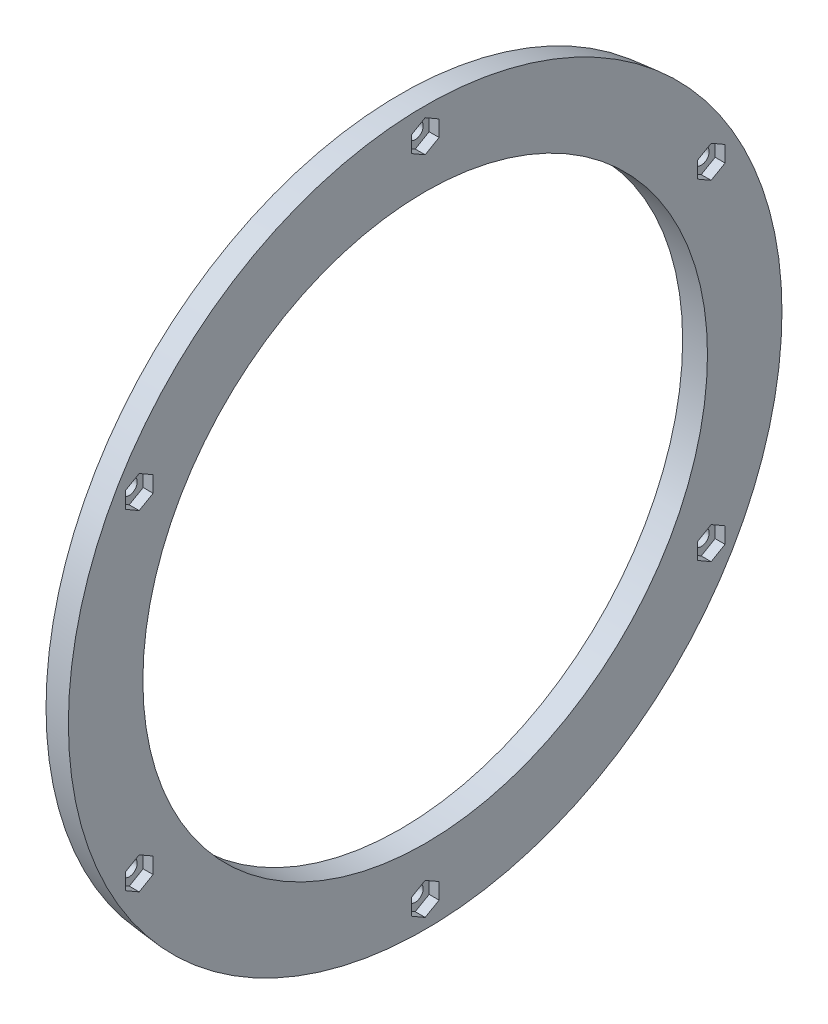
SolidWorks part; units mm, degrees
material "Balsa"
ref_plane "Front Plane" through (0, 0, 0) normal (0, 0, 1) x (1, 0, 0)
ref_plane "Top Plane" through (0, 0, 0) normal (0, 1, 0) x (1, 0, 0)
ref_plane "Right Plane" through (0, 0, 0) normal (1, 0, 0) x (0, 0, -1)
sketch "Sketch1" plane through (0, 0, 0) normal (1, 0, 0) x (0, 0, -1)
  circle A0 centre (0, 0) radius 71.85
  circle A1 centre (0, 0) radius 56.85
  dimension "D1" = 143.7
  dimension "D2" = 15
extrude "Boss-Extrude1" add sketch "Sketch1" along normal blind 5
sketch "Sketch2" plane through (5, 0, 0) normal (1, 0, 0) x (0, 0, -1)
  line L0 (54.7907, 31.6334) -> (57.5907, 30.0168)
  line L1 (0, 63.2668) -> (2.8, 64.8834)
  line L2 (2.8, 64.8834) -> (2.8, 68.1166)
  line L3 (2.8, 68.1166) -> (0, 69.7332)
  line L4 (0, 69.7332) -> (-2.8, 68.1166)
  line L5 (-2.8, 68.1166) -> (-2.8, 64.8834)
  line L6 (-2.8, 64.8834) -> (0, 63.2668)
  line L7 (57.5907, 30.0168) -> (60.3907, 31.6334)
  line L8 (60.3907, 31.6334) -> (60.3907, 34.8666)
  line L9 (60.3907, 34.8666) -> (57.5907, 36.4832)
  line L10 (57.5907, 36.4832) -> (54.7907, 34.8666)
  line L11 (54.7907, 34.8666) -> (54.7907, 31.6334)
  line L12 (54.7907, -31.6334) -> (54.7907, -34.8666)
  line L13 (54.7907, -34.8666) -> (57.5907, -36.4832)
  line L14 (57.5907, -36.4832) -> (60.3907, -34.8666)
  line L15 (60.3907, -34.8666) -> (60.3907, -31.6334)
  line L16 (60.3907, -31.6334) -> (57.5907, -30.0168)
  line L17 (57.5907, -30.0168) -> (54.7907, -31.6334)
  line L18 (0, -63.2668) -> (-2.8, -64.8834)
  line L19 (-2.8, -64.8834) -> (-2.8, -68.1166)
  line L20 (-2.8, -68.1166) -> (0, -69.7332)
  line L21 (0, -69.7332) -> (2.8, -68.1166)
  line L22 (2.8, -68.1166) -> (2.8, -64.8834)
  line L23 (2.8, -64.8834) -> (0, -63.2668)
  line L24 (-54.7907, -31.6334) -> (-57.5907, -30.0168)
  line L25 (-57.5907, -30.0168) -> (-60.3907, -31.6334)
  line L26 (-60.3907, -31.6334) -> (-60.3907, -34.8666)
  line L27 (-60.3907, -34.8666) -> (-57.5907, -36.4832)
  line L28 (-57.5907, -36.4832) -> (-54.7907, -34.8666)
  line L29 (-54.7907, -34.8666) -> (-54.7907, -31.6334)
  line L30 (-54.7907, 31.6334) -> (-54.7907, 34.8666)
  line L31 (-54.7907, 34.8666) -> (-57.5907, 36.4832)
  line L32 (-57.5907, 36.4832) -> (-60.3907, 34.8666)
  line L33 (-60.3907, 34.8666) -> (-60.3907, 31.6334)
  line L34 (-60.3907, 31.6334) -> (-57.5907, 30.0168)
  line L35 (-57.5907, 30.0168) -> (-54.7907, 31.6334)
  circle A0 centre (0, 66.5) radius 2.8 construction
  circle A1 centre (57.5907, 33.25) radius 2.8 construction
  circle A2 centre (57.5907, -33.25) radius 2.8 construction
  circle A3 centre (0, -66.5) radius 2.8 construction
  circle A4 centre (-57.5907, -33.25) radius 2.8 construction
  circle A5 centre (-57.5907, 33.25) radius 2.8 construction
  point P52 (0, 0)
  dimension "D1" = 5.6
  dimension "D2" = 66.5
  dimension "D3" = 6
extrude "Cut-Extrude1" cut sketch "Sketch2" against normal blind 2
sketch "Sketch3" plane through (5, 0, 0) normal (1, 0, 0) x (0, 0, -1)
  line L0 (0, 0) -> (0, 66.5) construction
  circle A0 centre (0, 66.5) radius 1.6
  circle A1 centre (57.5907, 33.25) radius 1.6
  circle A2 centre (57.5907, -33.25) radius 1.6
  circle A3 centre (0, -66.5) radius 1.6
  circle A4 centre (-57.5907, -33.25) radius 1.6
  circle A5 centre (-57.5907, 33.25) radius 1.6
  point P17 (0, 0)
  point P20 (-1.299, 0.75)
  dimension "D1" = 66.5
  dimension "D2" = 3.2
  dimension "D3" = 6
extrude "Cut-Extrude2" cut sketch "Sketch3" against normal up to next
sketch "Sketch4" plane through (0, 0, 0) normal (0, 0, 1) x (1, 0, 0)
  line L0 (0, 0) -> (0, -71.35) construction
  line L1 (0, -71.35) -> (0, -71.85)
  line L2 (0, -71.85) -> (5, -71.85)
  line L3 (5, -71.85) -> (0, -71.35)
  dimension "D1" = 71.85
  dimension "D2" = 0.5
  dimension "D3" = 5
ref_axis "Axis1" through (0, 0, 0) along (1, 0, 0)
revolve "Cut-Revolve1" cut sketch "Sketch4" angle 360 about axis through (0, 0, 0) along (1, 0, 0)
equation "\"D1@Sketch4\"=143.7/2"
